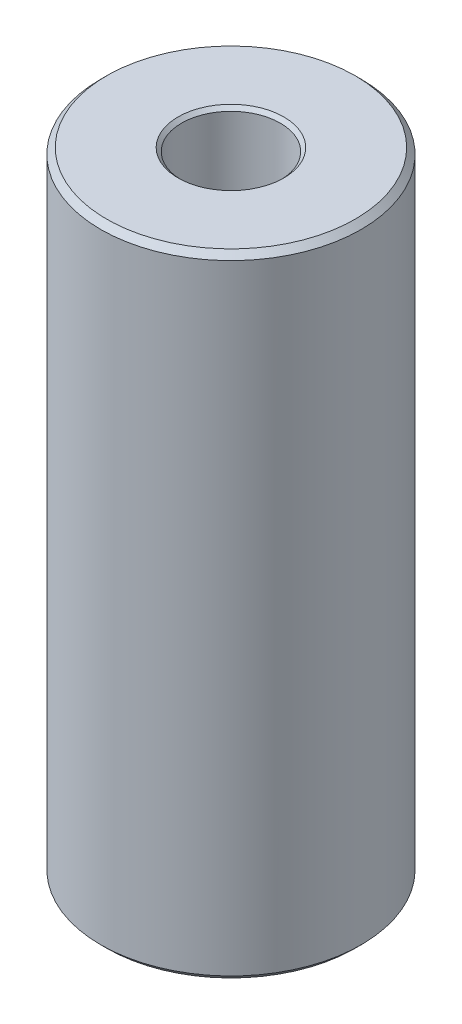
SolidWorks part; units mm, degrees
ref_plane "Front Plane" through (0, 0, 0) normal (0, 0, 1) x (1, 0, 0)
ref_plane "Top Plane" through (0, 0, 0) normal (0, 1, 0) x (1, 0, 0)
ref_plane "Right Plane" through (0, 0, 0) normal (1, 0, 0) x (0, 0, -1)
sketch "Sketch1" plane through (0, 0, 0) normal (1, 0, 0) x (0, 0, -1)
  line L0 (3.9751, 0) -> (5.5626, 0)
  line L1 (5.5626, 0) -> (5.5626, 26.9748)
  line L2 (5.5626, 26.9748) -> (2.1082, 26.9748)
  line L3 (2.1082, 26.9748) -> (2.1082, 4.6777)
  line L4 (2.1082, 4.6777) -> (3.9751, 3.556)
  line L5 (3.9751, 3.556) -> (3.9751, 0)
  line L6 (0, -4.1411) -> (0, -13.3303) construction
  dimension "D1" = 7.9502
  dimension "D2" = 11.1252
  dimension "D3" = 3.556
  dimension "D4" = 26.9748
  dimension "D5" = 4.2164
  dimension "D6" = 59
revolve "Revolve1" add sketch "Sketch1" angle 360 about L6
chamfer "Chamfer1" distance 0.254 angle 45 2 edges at (0, 0, 5.5626) (0, 26.9748, 5.5626)
chamfer "Chamfer2" distance 0.1524 angle 45 2 edges at (0, 26.9748, 2.1082) (0, 0, 3.9751)
